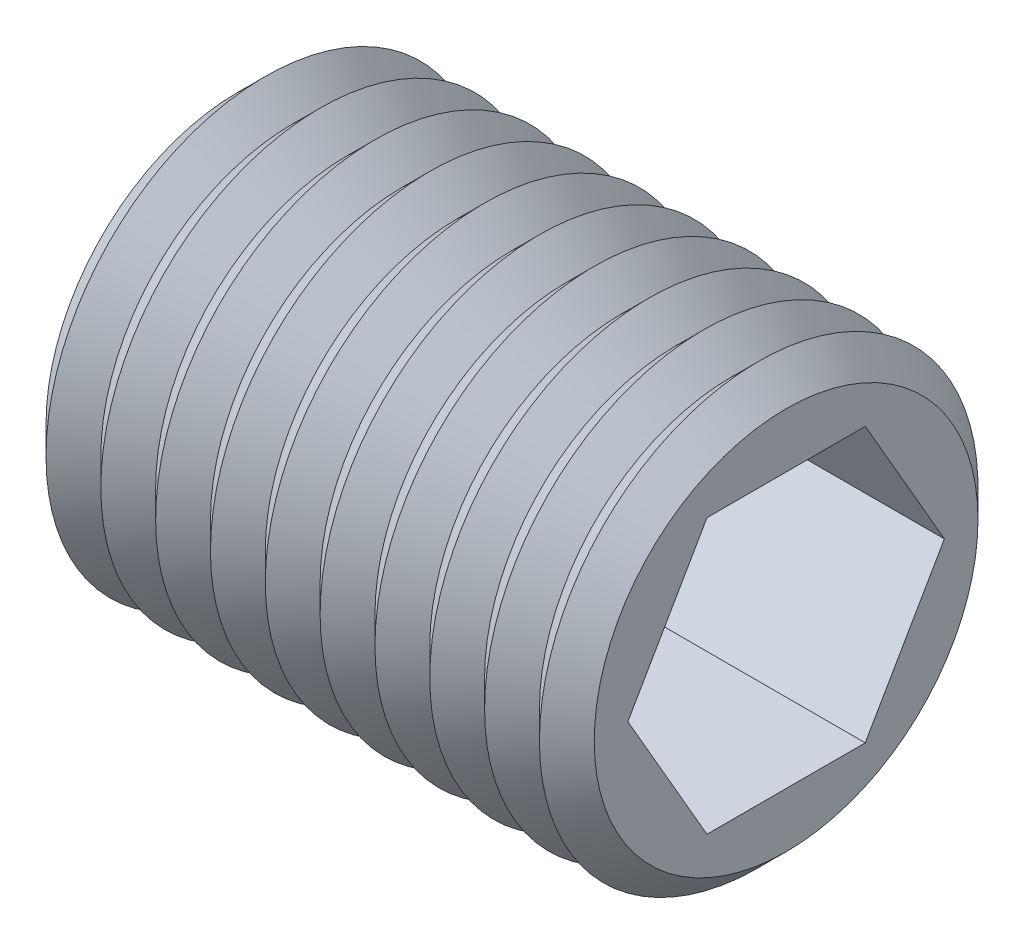
SolidWorks part; units mm, degrees
ref_plane "前视基准面" through (0, 0, 0) normal (0, 0, 1) x (1, 0, 0)
ref_plane "上视基准面" through (0, 0, 0) normal (0, 1, 0) x (1, 0, 0)
ref_plane "右视基准面" through (0, 0, 0) normal (1, 0, 0) x (0, 0, -1)
sketch "草图1" plane through (0, 0, 0) normal (0, 0, 1) x (1, 0, 0)
  line B0 (10, 0) -> (10, 3.5)
  line B1 (0, 0) -> (10, 0)
  line B2 (10, 3.5) -> (9.5, 4)
  line B3 (0, 3.5) -> (0, 0)
  line B4 (0.5, 4) -> (0, 3.5)
  line B5 (9, 3.5) -> (9.5, 4)
  line B6 (9, 3.5) -> (8.5, 4)
  line B7 (8, 3.5) -> (8.5, 4)
  line B8 (8, 3.5) -> (7.5, 4)
  line B9 (7, 3.5) -> (7.5, 4)
  line B10 (7, 3.5) -> (6.5, 4)
  line B11 (6, 3.5) -> (6.5, 4)
  line B12 (6, 3.5) -> (5.5, 4)
  line B13 (5, 3.5) -> (5.5, 4)
  line B14 (5, 3.5) -> (4.5, 4)
  line B15 (4, 3.5) -> (4.5, 4)
  line B16 (4, 3.5) -> (3.5, 4)
  line B17 (3, 3.5) -> (3.5, 4)
  line B18 (3, 3.5) -> (2.5, 4)
  line B19 (2, 3.5) -> (2.5, 4)
  line B20 (2, 3.5) -> (1.5, 4)
  line B21 (1, 3.5) -> (1.5, 4)
  line B22 (1, 3.5) -> (0.5, 4)
sketch_block_instance "A$C5B794759-1"
sketch_block "A$C5B794759"
revolve "旋转1" add sketch "草图1" angle 360 about L1
sketch "草图3" plane through (10, 0, 0) normal (1, 0, 0) x (0, 0, -1)
  line L1 (2.8868, 0) -> (1.4434, 2.5)
  line L2 (1.4434, 2.5) -> (-1.4434, 2.5)
  line L3 (-1.4434, 2.5) -> (-2.8868, 0)
  line L4 (-2.8868, 0) -> (-1.4434, -2.5)
  line L5 (-1.4434, -2.5) -> (1.4434, -2.5)
  line L6 (1.4434, -2.5) -> (2.8868, 0)
  circle A0 centre (0, 0) radius 2.5 construction
extrude "切除-拉伸1" cut sketch "草图3" against normal blind 5
